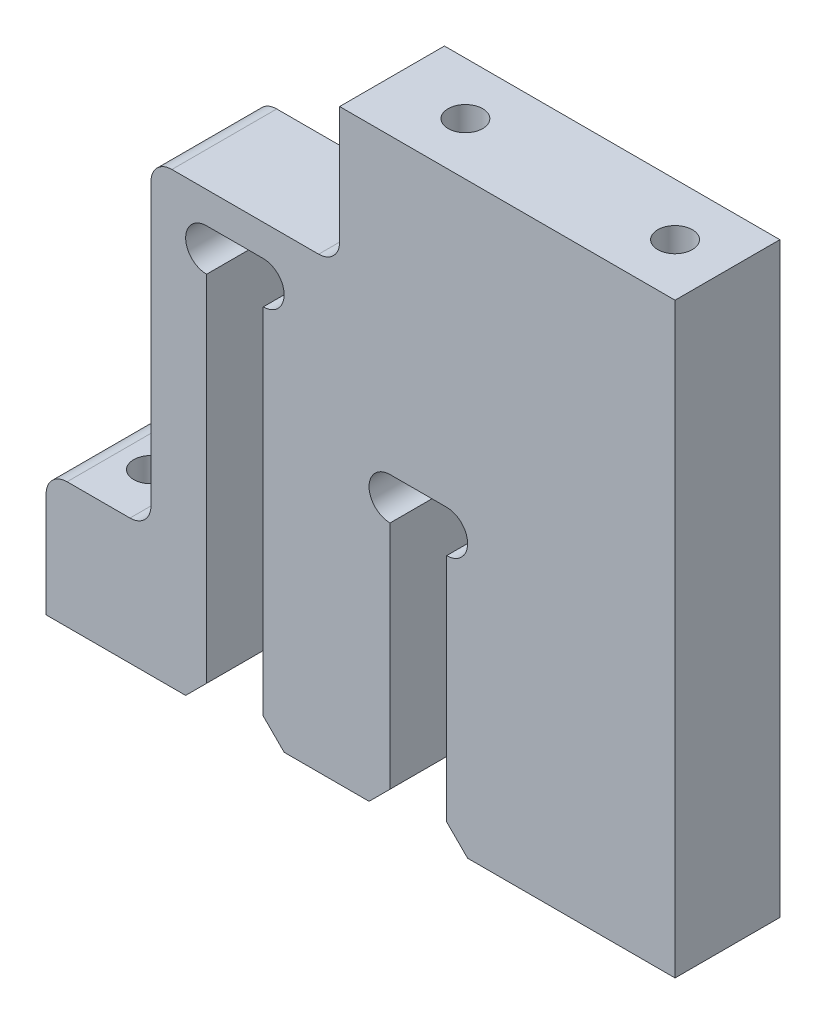
SolidWorks part; units mm, degrees
material "防静电研磨黑纤"
ref_plane "前视基准面" through (0, 0, 0) normal (0, 0, 1) x (1, 0, 0)
ref_plane "上视基准面" through (0, 0, 0) normal (0, 1, 0) x (1, 0, 0)
ref_plane "右视基准面" through (0, 0, 0) normal (1, 0, 0) x (0, 0, -1)
sketch "草图1" plane through (0, 0, 0) normal (0, 0, 1) x (1, 0, 0)
  line L1 (-30, 28) -> (30, 28)
  line L2 (-30, 28) -> (-30, -28)
  line L3 (-30, -28) -> (30, -28)
  line L4 (30, 28) -> (30, -28)
  line L5 (-30, 28) -> (30, -28) construction
  line L6 (-30, -28) -> (30, 28) construction
  point P0 (0, 0)
  dimension "D1" = 56
  dimension "D2" = 60
extrude "凸台-拉伸1" add sketch "草图1" along normal mid plane 10
sketch "草图3" plane through (0, 0, 5) normal (0, 0, 1) x (1, 0, 0)
  line L0 (5.51, 0) -> (5.51, -28) construction
  line L1 (2.81, 0) -> (8.21, 0)
  line L2 (2.81, 0) -> (2.81, -28)
  line L3 (2.81, -28) -> (8.21, -28)
  line L4 (8.21, 0) -> (8.21, -28)
  line L9 (-30, -28) -> (30, -28) construction
  line L10 (0, 0) -> (0, -28) construction
  line L16 (-14.69, -28) -> (-9.29, -28)
  line L17 (-14.69, -28) -> (-14.69, 11.8)
  line L18 (-14.69, 11.8) -> (-9.29, 11.8)
  line L19 (-9.29, -28) -> (-9.29, 11.8)
  line L20 (-14.69, -28) -> (-9.29, 11.8) construction
  line L21 (-14.69, 11.8) -> (-9.29, -28) construction
  point P11 (-11.99, -8.1)
  dimension "D1" = 5.4
  dimension "D2" = 5.51
  dimension "D3" = 28
  dimension "D4" = 11.99
  dimension "D5" = 39.8
extrude "切除-拉伸1" cut sketch "草图3" against normal through all
hole_wizard "M4 螺纹孔1" positions "草图4" profile "草图5" tap size "M4" standard "ISO"
sketch "草图4" plane through (0, -28, 0) normal (0, -1, 0) x (-1, 0, 0)
  point P0 (25, 0)
  point P2 (-25, 0)
sketch "草图5" plane through (-25, -28, 0) normal (1, 0, 0) x (0, 0, -1)
  line L0 (0, 0) -> (0, 13.0914)
  line L1 (0, 13.0914) -> (1.65, 12.1)
  line L2 (1.65, 12.1) -> (1.65, 0)
  line L5 (1.65, 0) -> (0, 0)
  line L10 (0, 13.0914) -> (-1.65, 12.1) construction
  line L11 (0, -6.35) -> (0, 107.95) construction
  dimension "螺纹孔钻头直径" = 3.3
  dimension "螺纹孔钻头深度" = 12.1
  dimension "导头角度" = 118
cosmetic thread "孔螺蚊线1" parameters "D1"=10, "D2"=4
cosmetic thread "孔螺蚊线2" parameters "D1"=10, "D2"=4
hole_wizard "大小mm 暗销孔1" positions "草图8" profile "草图9" hole size "Ø4.0" standard "ISO"
sketch "草图8" plane through (0, 0, 5) normal (0, 0, 1) x (1, 0, 0)
  line L2 (2.81, 0) -> (2.81, -28) construction
  line L3 (8.21, -28) -> (8.21, 0) construction
  line L5 (8.21, 0) -> (2.81, 0) construction
  line L6 (-14.69, 11.8) -> (-14.69, -28) construction
  line L7 (-9.29, -28) -> (-9.29, 11.8) construction
  line L8 (-9.29, 11.8) -> (-14.69, 11.8) construction
  point P0 (-14.69, 9.8)
  point P4 (-9.29, 9.8)
  point P8 (2.81, -2)
  point P12 (8.21, -2)
  dimension "D1" = 2
  dimension "D3" = 2
  dimension "D4" = 2
sketch "草图9" plane through (-14.69, 9.8, 5) normal (1, 0, 0) x (0, -1, 0)
  line L0 (0, 0) -> (0, 14.2017)
  line L1 (0, 14.2017) -> (2, 13)
  line L2 (2, 13) -> (2, 0)
  line L5 (2, 0) -> (0, 0)
  line L10 (0, 14.2017) -> (-2, 13) construction
  line L11 (0, -6.35) -> (0, 107.95) construction
  dimension "孔直径" = 4
  dimension "孔深度" = 13
  dimension "导头角度" = 118
chamfer "倒角1" distance 2 angle 45 4 edges at (8.21, -28, 0) (2.81, -28, 0) (-14.69, -28, 0) (-9.29, -28, 0)
sketch "草图10" plane through (0, 0, 5) normal (0, 0, 1) x (1, 0, 0)
  line L0 (30, 28) -> (-30, 28) construction
  line L1 (-30, 28) -> (0, 28)
  line L2 (-30, 28) -> (-30, 7)
  line L3 (-30, 7) -> (0, 7)
  line L4 (0, 28) -> (0, 7)
  line L5 (-30, 28) -> (0, 7) construction
  line L6 (-30, 7) -> (0, 28) construction
  line L8 (30, -28) -> (30, 28) construction
  line L9 (-30, 28) -> (-30, -28) construction
  point P0 (-15, 17.5)
  dimension "D1" = 21
  dimension "D3" = 30
extrude "切除-拉伸2" [suppressed] cut sketch "草图10" against normal blind 10
sketch "草图12" [suppressed] plane through (0, 0, -5) normal (0, 0, 1) x (1, 0, 0)
  line L1 (-10, 7) -> (0, 7)
  line L2 (-10, 7) -> (-10, 2.5)
  line L3 (-10, 2.5) -> (0, 2.5)
  line L4 (0, 7) -> (0, 2.5)
  dimension "D1" = 4.5
extrude "切除-拉伸3" [suppressed] cut sketch "草图12" along normal blind 4
fillet "圆角1" [suppressed] radius 1.6
sketch "草图13" plane through (0, 0, 5) normal (0, 0, 1) x (1, 0, 0)
  line L0 (-30, 28) -> (-2, 28)
  line L4 (-20, 14.8) -> (-20, -16)
  line L6 (-20, -16) -> (-30, -16)
  line L7 (-30, -16) -> (-30, 28)
  line L9 (-20, 14.8) -> (-2, 14.8)
  line L10 (-2, 14.8) -> (-2, 28)
  line L11 (30, -28) -> (30, 28) construction
  line L12 (-9.29, 11.8) -> (-14.69, 11.8) construction
  line L13 (-30, -28) -> (-16.69, -28) construction
  dimension "D1" = 32
  dimension "D2" = 3
  dimension "D3" = 10
  dimension "D4" = 12
extrude "切除-拉伸4" cut sketch "草图13" against normal through all
fillet "圆角2" radius 2 4 edges at (-30, -16, 0) (-20, -16, 0) (-20, 14.8, 0) (-2, 14.8, 0)
hole_wizard "M4 螺纹孔2" positions "草图6" profile "草图7" tap size "M4" standard "ISO"
sketch "草图6" plane through (0, 28, 0) normal (0, 1, 0) x (1, 0, 0)
  point P3 (25, 0)
  point P6 (5, 0)
  dimension "D1" = 20
sketch "草图7" plane through (25, 28, 0) normal (1, 0, 0) x (0, 0, 1)
  line L0 (0, 0) -> (0, 13.0914)
  line L1 (0, 13.0914) -> (1.65, 12.1)
  line L2 (1.65, 12.1) -> (1.65, 0)
  line L5 (1.65, 0) -> (0, 0)
  line L10 (0, 13.0914) -> (-1.65, 12.1) construction
  line L11 (0, -6.35) -> (0, 107.95) construction
  dimension "螺纹孔钻头直径" = 3.3
  dimension "螺纹孔钻头深度" = 12.1
  dimension "导头角度" = 118
cosmetic thread "孔螺蚊线3" parameters "D1"=10, "D2"=4
cosmetic thread "孔螺蚊线4" parameters "D1"=10, "D2"=4
